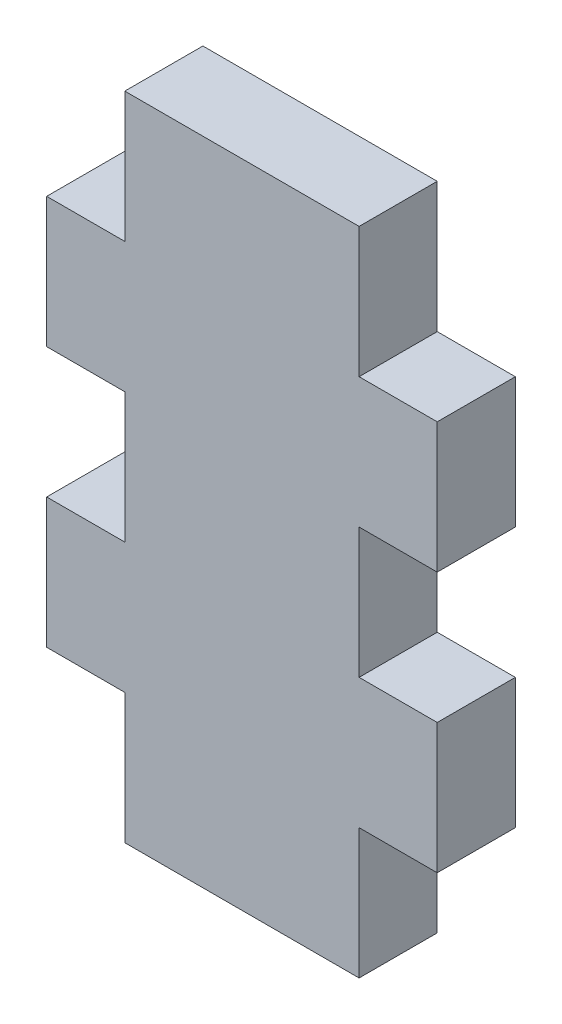
SolidWorks part; units mm, degrees
ref_plane "Front Plane" through (0, 0, 0) normal (0, 0, 1) x (1, 0, 0)
ref_plane "Top Plane" through (0, 0, 0) normal (0, 1, 0) x (1, 0, 0)
ref_plane "Right Plane" through (0, 0, 0) normal (1, 0, 0) x (0, 0, -1)
sketch "Sketch1" plane through (0, 0, 0) normal (0, 0, 1) x (1, 0, 0)
  line L1 (0, 0) -> (76.2, 0)
  line L2 (0, 0) -> (0, 127)
  line L3 (0, 127) -> (76.2, 127)
  line L4 (76.2, 0) -> (76.2, 127)
  dimension "D1" = 76.2
  dimension "D2" = 127
extrude "Boss-Extrude1" add sketch "Sketch1" along normal blind 15.24 contours L2 L1 L4 L3
sketch "Sketch13" plane through (0, 0, 15.24) normal (0, 0, 1) x (1, 0, 0)
  line L0 (0, 0) -> (0, 127) construction
  line L1 (0, 127) -> (15.24, 127)
  line L2 (0, 127) -> (0, 101.6)
  line L3 (0, 101.6) -> (15.24, 101.6)
  line L4 (15.24, 127) -> (15.24, 101.6)
  line L5 (0, 76.2) -> (15.24, 76.2)
  line L6 (0, 76.2) -> (0, 50.8)
  line L7 (0, 50.8) -> (15.24, 50.8)
  line L8 (15.24, 76.2) -> (15.24, 50.8)
  line L9 (76.2, 0) -> (76.2, 127) construction
  line L10 (0, 0) -> (15.24, 0)
  line L11 (0, 0) -> (0, 25.4)
  line L12 (0, 25.4) -> (15.24, 25.4)
  line L13 (15.24, 0) -> (15.24, 25.4)
  line L14 (76.2, 127) -> (60.96, 127)
  line L15 (76.2, 127) -> (76.2, 101.6)
  line L16 (76.2, 101.6) -> (60.96, 101.6)
  line L17 (60.96, 127) -> (60.96, 101.6)
  line L18 (76.2, 76.2) -> (60.96, 76.2)
  line L19 (76.2, 76.2) -> (76.2, 50.8)
  line L20 (76.2, 50.8) -> (60.96, 50.8)
  line L21 (60.96, 76.2) -> (60.96, 50.8)
  line L22 (0, 0) -> (76.2, 0) construction
  line L23 (76.2, 25.4) -> (60.96, 25.4)
  line L24 (76.2, 25.4) -> (76.2, 0)
  line L25 (76.2, 0) -> (60.96, 0)
  line L26 (60.96, 25.4) -> (60.96, 0)
  line L27 (15.24, 101.6) -> (15.24, 76.2) construction
  line L28 (15.24, 50.8) -> (15.24, 25.4) construction
  line L29 (60.96, 101.6) -> (60.96, 76.2) construction
  line L30 (60.96, 50.8) -> (60.96, 25.4) construction
  dimension "D1" = 15.24
  dimension "D2" = 15.24
extrude "Cut-Extrude1" cut sketch "Sketch13" against normal blind 15.24
equation "\"MDF\"= .6"
equation "\"Foamcore\"= .1"
equation "\"GMaterial\"= \"MDF\""
equation "\"D1@Boss-Extrude1\"=\"GMaterial\""
equation "\"D1@Cut-Extrude9\"=\"GMaterial\""
equation "\"D1@Sketch13\"=\"GMaterial\""
equation "\"D2@Sketch13\"=\"GMaterial\""
equation "\"D1@Cut-Extrude1\"=\"GMaterial\""
